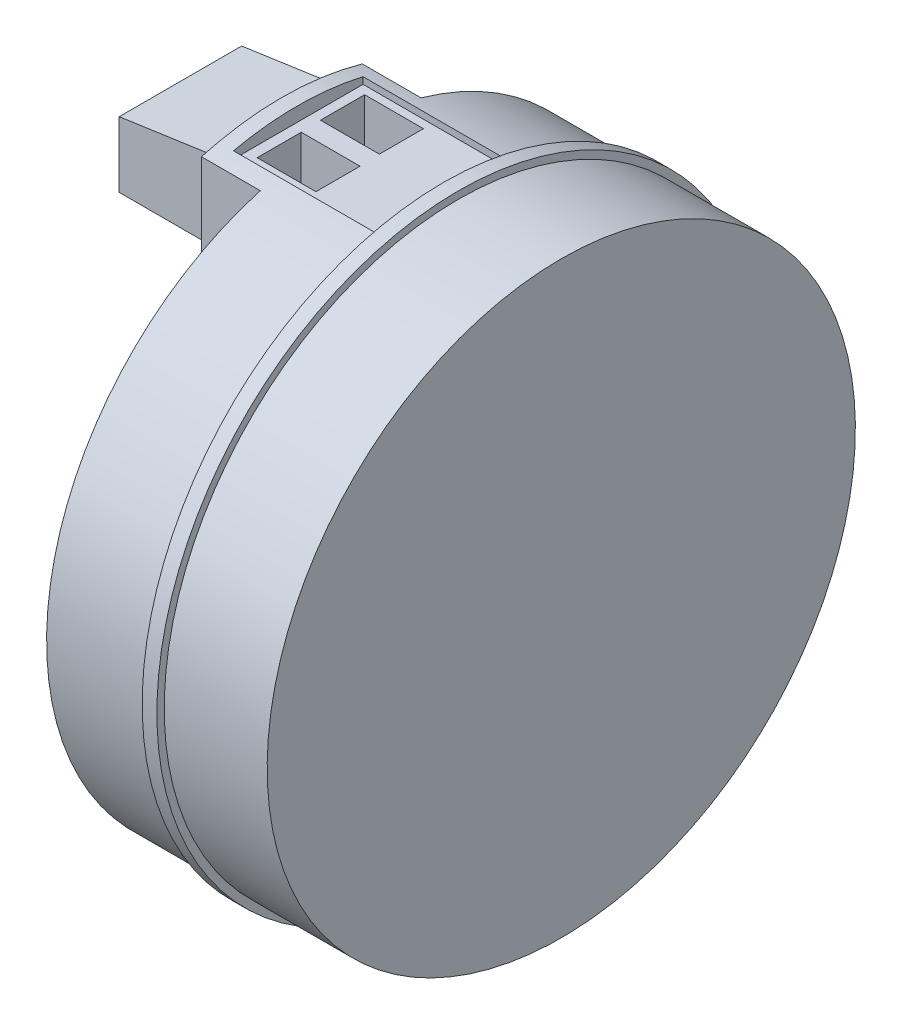
SolidWorks part; units mm, degrees
ref_plane "Front Plane" through (0, 0, 0) normal (0, 0, 1) x (1, 0, 0)
ref_plane "Top Plane" through (0, 0, 0) normal (0, 1, 0) x (1, 0, 0)
ref_plane "Right Plane" through (0, 0, 0) normal (1, 0, 0) x (0, 0, -1)
sketch "Sketch1" plane through (0, 0, 0) normal (0, 0, 1) x (1, 0, 0)
  line L0 (71.0941, 0) -> (-71.0941, 0) construction
  line L1 (0, 78.1021) -> (0, -78.1021) construction
  line L2 (27.7761, 0) -> (27.7761, -20)
  line L3 (27.7761, -20) -> (53.6761, -20)
  line L4 (53.6761, -20) -> (53.6761, 0)
  line L5 (27.7761, 0) -> (53.6761, 0)
  point P4 (0, 0)
  point P8 (0, 0)
revolve "Revolve1" add sketch "Sketch1" angle 360 about L0
sketch "Sketch2" plane through (27.7761, 0, 0) normal (-1, 0, 0) x (0, 0, 1)
  line L0 (-7.2417, 18.6429) -> (7.6214, 18.4909)
  line L1 (7.6214, 18.4909) -> (7.6214, 13.0353)
  line L2 (7.6214, 13.0353) -> (-7.2417, 13.0353)
  line L3 (-7.2417, 13.0353) -> (-7.2417, 18.6429)
  circle A0 centre (0, 0) radius 20
  circle M2 centre (0, 0) radius 20
extrude "Cut-Extrude1" cut sketch "Sketch2" against normal blind 6.9 contours L0 M2 | L2 L3 L1 M2
sketch "Sketch3" plane through (0, 0, 7.6214) normal (0, 0, 1) x (1, 0, 0)
  line L0 (34.6761, 13.0353) -> (27.7761, 13.0353)
  line L1 (27.7761, 13.0353) -> (27.7761, 17.4953)
  line L2 (27.7761, 17.4953) -> (34.6761, 18.4909)
  line L3 (27.7761, 17.4953) -> (27.7761, 19.0754)
  line L6 (27.7761, 13.0353) -> (34.6761, 13.0353)
  line L7 (34.6761, 18.4909) -> (34.6761, 13.0353)
  line L8 (27.7761, 19.0754) -> (34.6761, 18.6676)
  line L9 (34.6761, 18.6676) -> (34.6761, 18.4909)
  line M8 (27.7761, 18.4909) -> (27.7761, 13.0353)
  line M11 (34.6761, 18.4909) -> (27.7761, 18.4909)
extrude "Cut-Extrude3" cut sketch "Sketch3" against normal blind 37.9 contours L2 M8 M11 | L9 L8 L3 M11
sketch "Sketch4" plane through (34.6761, 0, 0) normal (-1, 0, 0) x (0, 0, 1)
  line L3 (-5.4668, 5.1346) -> (-5.4668, 19.2384)
  line L5 (5.4668, 5.1346) -> (5.4668, 19.2384)
  circle A0 centre (0, 0) radius 20
  arc A1 (-5.4668, 5.1346) -> (5.4668, 5.1346) centre (0, 0) ccw
  point P6 (0.1899, 17.4953)
  point P10 (0, 0)
  circle M2 centre (0, 0) radius 20
  line M3 (7.6214, 18.4909) -> (7.6214, 13.0353)
  line M4 (7.6214, 13.0353) -> (-7.2417, 13.0353)
  line M5 (-7.2417, 13.0353) -> (-7.2417, 18.4909)
  line M6 (-7.2417, 18.4909) -> (7.6214, 18.4909)
extrude "Cut-Extrude4" cut sketch "Sketch4" against normal blind 4 contours A1 L3 L5 M4 M5 M6 M2 M3
sketch "Sketch5" plane through (27.7761, 0, 0) normal (-1, 0, 0) x (0, 0, 1)
  line L0 (0, 0) -> (0, 29.7867) construction
  line L1 (4.1624, 13.0353) -> (-4.1624, 13.0353)
  line L3 (7.6214, 13.0353) -> (-7.2417, 13.0353) construction
  line L4 (-4.1624, 13.0353) -> (-4.1624, 19.4248)
  line L5 (-4.1624, 19.4248) -> (4.1624, 19.4248)
  line L6 (4.1624, 19.4248) -> (4.1624, 13.0353)
  line L7 (-7.2417, 13.0353) -> (7.6214, 13.0353)
  line L8 (7.6214, 13.0353) -> (7.6214, 19.4248)
  line L9 (7.6214, 19.4248) -> (-7.2417, 19.4248)
  line L10 (-7.2417, 19.4248) -> (-7.2417, 13.0353)
  point P5 (0, 13.0353)
  line M6 (7.6214, 13.0353) -> (7.6214, 17.4953)
  line M7 (7.6214, 17.4953) -> (-7.2417, 17.4953)
  line M8 (-7.2417, 17.4953) -> (-7.2417, 13.0353)
  line M9 (-7.2417, 13.0353) -> (7.6214, 13.0353)
extrude "Cut-Extrude5" cut sketch "Sketch5" against normal blind 6.9 contours L9 L10 L4 M7 | L4 M9 M7 M8 | L8 L9 L6 M7 | L6 M7 M9 M6
sketch "Sketch6" plane through (34.6761, 0, 0) normal (-1, 0, 0) x (0, 0, 1)
  line L0 (5.4668, 13.0353) -> (5.4668, 19.2384)
  line L1 (-7.2417, 18.4909) -> (-5.4668, 18.4909)
  line L2 (-7.2417, 18.4909) -> (-7.2417, 13.0353)
  line L3 (-7.2417, 13.0353) -> (-5.4668, 13.0353)
  line L4 (-5.4668, 18.4909) -> (-5.4668, 13.0353)
  line L5 (5.4668, 13.0353) -> (7.6214, 13.0353)
  line L6 (7.6214, 13.0353) -> (7.6214, 18.4909)
  circle A0 centre (0, 0) radius 20
  arc M6 (7.6214, 18.4909) -> (-5.4668, 19.2384) centre (0, 0) ccw
  line M14 (5.4668, 13.0353) -> (7.6214, 13.0353)
  line M15 (7.6214, 13.0353) -> (7.6214, 18.4909)
extrude "Cut-Extrude6" cut sketch "Sketch6" against normal blind 4 contours L0 M14 M15 M6 | L2 L1 L4 L3
ref_plane "Plane1" through (46.1761, 0, 0) normal (-1, 0, 0) x (0, 0, 1)
sketch "Sketch7" plane through (46.1761, 0, 0) normal (-1, 0, 0) x (0, 0, 1)
  circle A0 centre (0, 0) radius 20.5
extrude "Boss-Extrude1" add sketch "Sketch7" along normal mid plane 1
sketch "Sketch8" plane through (38.6761, 0, 0) normal (-1, 0, 0) x (0, 0, 1)
  line L1 (-17.9095, 7.2584) -> (-12.4588, 7.2584)
  line L2 (-17.9095, 7.2584) -> (-17.9095, -7.0915)
  line L3 (-17.9095, -7.0915) -> (-12.4588, -7.0915)
  line L4 (-12.4588, 7.2584) -> (-12.4588, -7.0915)
extrude "Cut-Extrude7" cut sketch "Sketch8" against normal blind 4
sketch "Sketch9" plane through (42.6761, 0, 0) normal (-1, 0, 0) x (0, 0, 1)
  line L1 (-17.3619, 6.7818) -> (-13.0065, 6.7818)
  line L2 (-17.3619, 6.7818) -> (-17.3619, -6.5482)
  line L3 (-17.3619, -6.5482) -> (-13.0065, -6.5482)
  line L4 (-13.0065, 6.7818) -> (-13.0065, -6.5482)
  line L5 (-17.9095, 7.2584) -> (-12.4588, 7.2584)
  line L6 (-17.9095, 7.2584) -> (-17.9095, -7.0915)
  line L7 (-17.9095, -7.0915) -> (-12.4588, -7.0915)
  line L8 (-12.4588, 7.2584) -> (-12.4588, -7.0915)
extrude "Boss-Extrude2" add sketch "Sketch9" along normal blind 3
sketch "Sketch10" plane through (42.6761, 0, 0) normal (-1, 0, 0) x (0, 0, 1)
  circle A0 centre (-15.8267, 4.1069) radius 0.25
  circle A1 centre (-15.8267, 1.6069) radius 0.25
  circle A2 centre (-15.8267, -3.3931) radius 0.25
  circle A3 centre (-15.8267, -0.8931) radius 0.25
extrude "Boss-Extrude3" add sketch "Sketch10" along normal blind 3
fillet "Fillet1" radius 0.1 1 edges at (39.6761, 4.1069, -15.5767)
fillet "Fillet2" radius 0.1 1 edges at (39.6761, 1.6069, -15.5767)
fillet "Fillet3" radius 0.1 1 edges at (39.6761, -0.8931, -15.5767)
fillet "Fillet4" radius 0.1 1 edges at (39.6761, -3.3931, -15.5767)
ref_plane "Plane2" through (0, 20, 0) normal (0, 1, 0) x (1, 0, 0)
sketch "Sketch11" plane through (0, 20, 0) normal (0, 1, 0) x (1, 0, 0)
  line L0 (45.6761, 20.5) -> (45.6761, -20.5) construction
  line L1 (35.7023, 4.491) -> (45.6761, 4.491)
  line L2 (35.7023, 4.491) -> (35.7023, -4.3189)
  line L3 (35.7023, -4.3189) -> (45.6761, -4.3189)
  line L4 (45.6761, 4.491) -> (45.6761, -4.3189)
extrude "Cut-Extrude8" cut sketch "Sketch11" against normal up to surface (6.9647 mm away) up to face at (31.2261, 13.0353, 0)
sketch "Sketch12" plane through (0, 13.0353, 0) normal (0, 1, 0) x (1, 0, 0)
  line L0 (36.4218, -0.4288) -> (40.4218, -0.4288)
  line L1 (35.7023, 4.491) -> (45.6761, 4.491)
  line L2 (35.7023, 4.491) -> (35.7023, -4.3189)
  line L3 (35.7023, -4.3189) -> (45.6761, -4.3189)
  line L4 (45.6761, 4.491) -> (45.6761, -4.3189)
  line L5 (36.3669, 3.9354) -> (40.3669, 3.9354)
  line L6 (36.3669, 3.9354) -> (36.3669, 0.9354)
  line L7 (36.3669, 0.9354) -> (40.3669, 0.9354)
  line L8 (40.3669, 3.9354) -> (40.3669, 0.9354)
  line L9 (36.4218, -0.4288) -> (36.4218, -3.4288)
  line L10 (36.4218, -3.4288) -> (40.4218, -3.4288)
  line L11 (40.4218, -0.4288) -> (40.4218, -3.4288)
extrude "Boss-Extrude4" add sketch "Sketch12" along normal blind 6 contours L2 L1 L4 L3 | L6 L5 L8 L7 | L0 L11 L10 L9
sketch "Sketch14" plane through (36.4218, 0, 0) normal (1, 0, 0) x (0, 0, -1)
  line L3 (0.0882, 6.0707) -> (0.0882, 19.9998) construction
  arc A0 (4.491, 19.4893) -> (-4.3189, 19.5281) centre (0, 0) ccw construction
  circle A1 centre (-1.9288, 16.0353) radius 1
  circle A2 centre (2.1053, 16.0353) radius 1
  point P3 (0.0882, 13.0353)
  point P9 (0.0882, 13.0353)
extrude "Cut-Extrude9" cut sketch "Sketch14" against normal blind 12
ref_plane "Plane3" through (26.7761, 0, 0) normal (-1, 0, 0) x (0, 0, 1)
sketch "Sketch15" plane through (26.7761, 0, 0) normal (-1, 0, 0) x (0, 0, 1)
  circle A0 centre (-2.1053, 16.0353) radius 1
